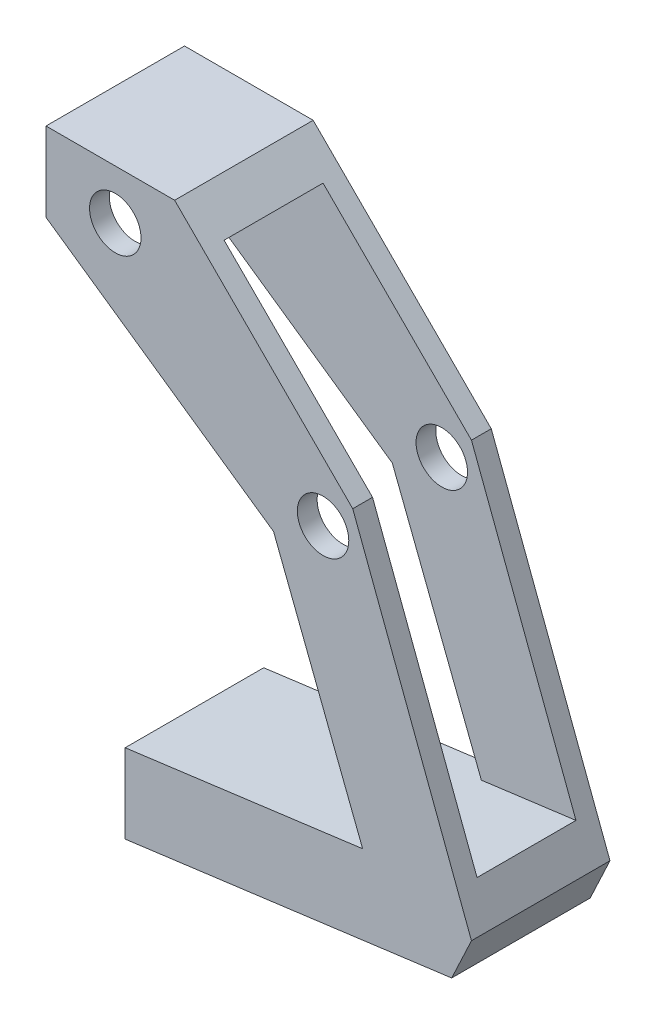
SolidWorks part; units mm, degrees
ref_plane "前视基准面" through (0, 0, 0) normal (0, 0, 1) x (1, 0, 0)
ref_plane "上视基准面" through (0, 0, 0) normal (0, 1, 0) x (1, 0, 0)
ref_plane "右视基准面" through (0, 0, 0) normal (1, 0, 0) x (0, 0, -1)
other "Configuration Table"
sketch "草图1" plane through (0, 0, 0) normal (0, 0, 1) x (1, 0, 0)
  line L0 (12, 60) -> (25, 60)
  line L1 (25, 60) -> (43, 42)
  line L2 (43, 42) -> (55, 10.1877)
  line L3 (55, 10.1877) -> (53, 5.9244)
  line L4 (53, 5.9244) -> (20, 1.5798)
  line L5 (20, 1.5798) -> (20, 9.5798)
  line L6 (20, 9.5798) -> (44, 12.7395)
  line L7 (44, 12.7395) -> (35, 36)
  line L8 (35, 36) -> (12, 52)
  line L9 (12, 52) -> (12, 60)
  dimension "x0" = 12
  dimension "x1" = 25
  dimension "x2" = 43
  dimension "x3" = 55
  dimension "x4" = 53
  dimension "x5" = 20
  dimension "x7" = 44
  dimension "x8" = 35
  dimension "y0" = 60
  dimension "y2" = 42
  dimension "y3" = 10.1877
  dimension "y4" = 5.9244
  dimension "y5" = 1.5798
  dimension "y6" = 9.5798
  dimension "y7" = 12.7395
  dimension "y8" = 36
  dimension "y9" = 52
extrude "Extrude" add sketch "草图1" along normal blind 14
ref_plane "Fork_midplane" through (0, 0, 7) normal (0, 0, 1) x (1, 0, 0)
sketch "草图3" plane through (0, 0, 7) normal (0, 0, 1) x (1, 0, 0)
  line L0 (-5, 6.2885) -> (65, 15.5042)
  line L1 (65, 15.5042) -> (65, 57)
  line L2 (65, 57) -> (-5, 57)
  line L3 (-5, 57) -> (-5, 6.2885)
  dimension "x0" = 5
  dimension "x1" = 65
  dimension "y0" = 6.2885
  dimension "y1" = 15.5042
  dimension "y2" = 57
extrude "Fork_above_mounting_foot" cut sketch "草图3" against normal mid plane 10
sketch "草图4" plane through (0, 0, 14) normal (0, 0, 1) x (1, 0, 0)
  circle A0 centre (40, 39) radius 2.6
  dimension "diameter" = 5.2
  dimension "x" = 40
  dimension "y" = 39
extrude "Outer_pivot_bore" cut sketch "草图4" against normal through all
sketch "草图5" plane through (0, 0, 14) normal (0, 0, 1) x (1, 0, 0)
  circle A0 centre (19, 55) radius 2.6
  dimension "diameter" = 5.2
  dimension "x" = 19
  dimension "y" = 55
extrude "Upper_hinge_bore" cut sketch "草图5" against normal through all
